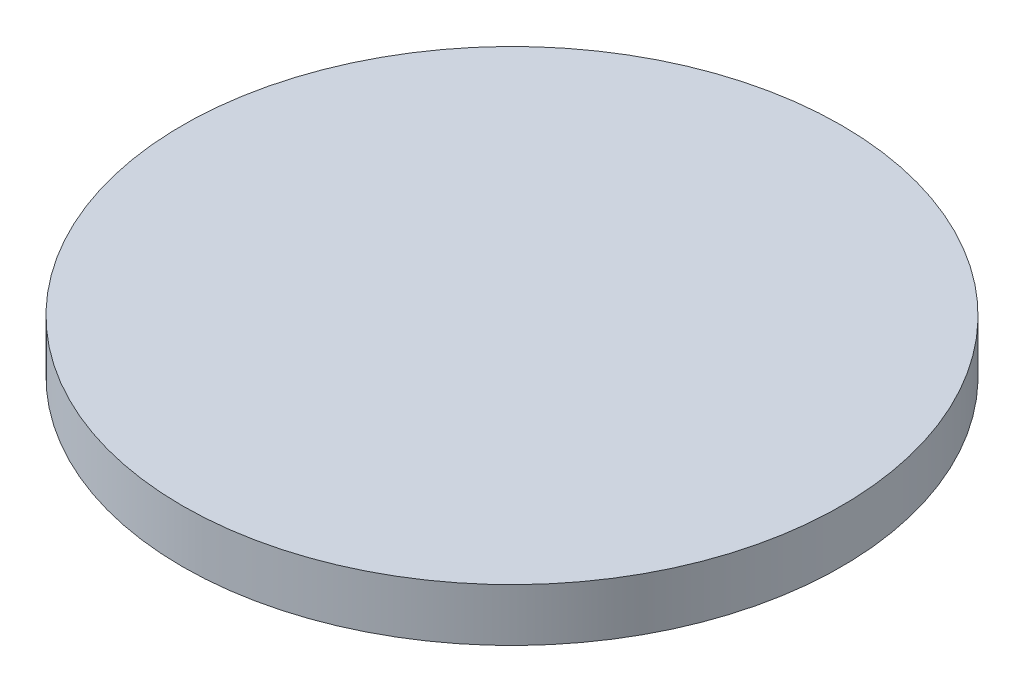
SolidWorks part; units mm, degrees
ref_plane "Front Plane" through (0, 0, 0) normal (0, 0, 1) x (1, 0, 0)
ref_plane "Top Plane" through (0, 0, 0) normal (0, 1, 0) x (1, 0, 0)
ref_plane "Right Plane" through (0, 0, 0) normal (1, 0, 0) x (0, 0, -1)
sketch "Sketch1" plane through (0, 0, 0) normal (0, 1, 0) x (1, 0, 0)
  circle A0 centre (0, 0) radius 62.5
extrude "Boss-Extrude1" add sketch "Sketch1" along normal blind 10
